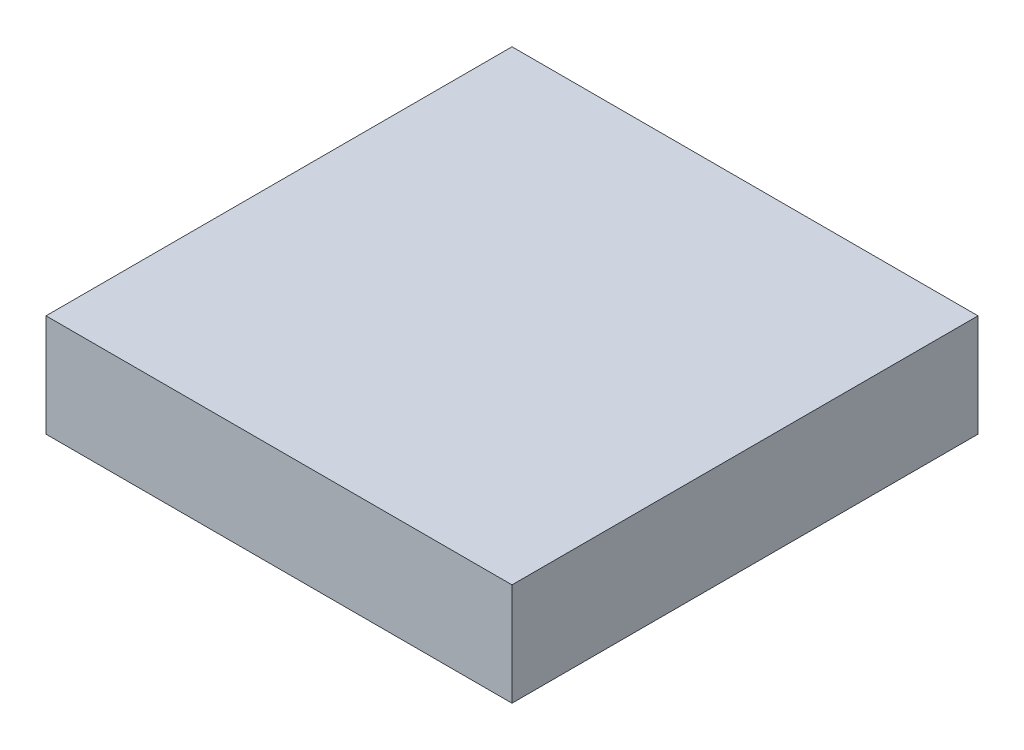
SolidWorks part; units mm, degrees
ref_plane "Спереди" through (0, 0, 0) normal (0, 0, 1) x (1, 0, 0)
ref_plane "Сверху" through (0, 0, 0) normal (0, 1, 0) x (1, 0, 0)
ref_plane "Справа" through (0, 0, 0) normal (1, 0, 0) x (0, 0, -1)
sketch "Эскиз1" plane through (0, 0, 0) normal (0, 1, 0) x (1, 0, 0)
  line L1 (-75, -75) -> (75, -75)
  line L2 (-75, -75) -> (-75, 75)
  line L3 (-75, 75) -> (75, 75)
  line L4 (75, -75) -> (75, 75)
  line L5 (-75, -75) -> (75, 75) construction
  line L6 (-75, 75) -> (75, -75) construction
  point P0 (0, 0)
extrude "Бобышка-Вытянуть1" add sketch "Эскиз1" along normal blind 33
sketch "Эскиз2" plane through (0, 0, 0) normal (0, -1, 0) x (-1, 0, 0)
  line L1 (69, 69) -> (-69, 69)
  line L2 (69, 69) -> (69, -69)
  line L3 (69, -69) -> (-69, -69)
  line L4 (-69, 69) -> (-69, -69)
  line L5 (69, 69) -> (-69, -69) construction
  line L6 (69, -69) -> (-69, 69) construction
  point P0 (0, 0)
extrude "Вырез-Вытянуть1" cut sketch "Эскиз2" against normal blind 12
